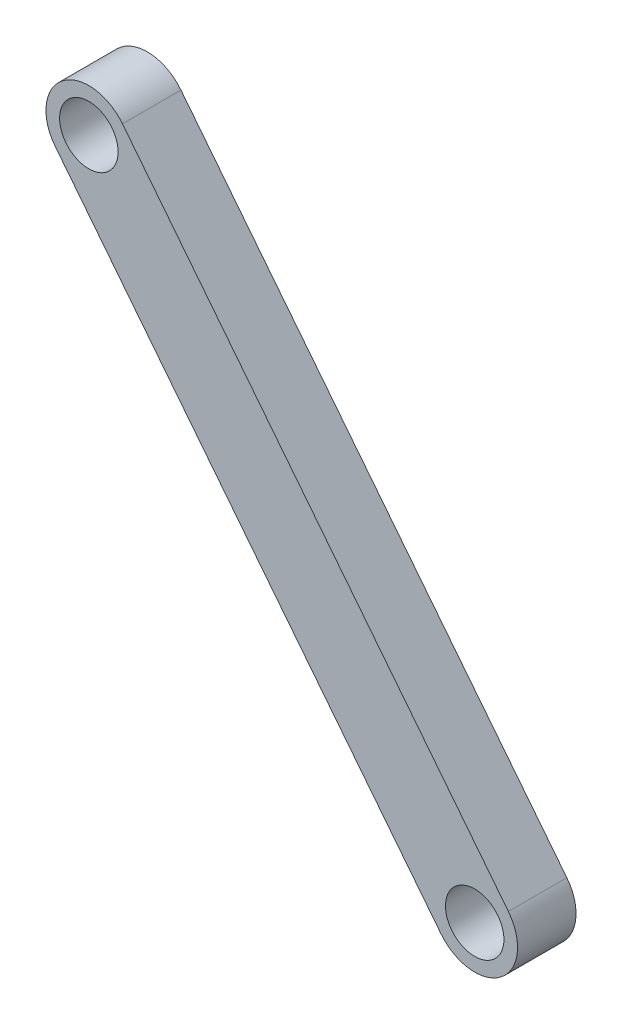
SolidWorks part; units mm, degrees
ref_plane "Plan de face" through (0, 0, 0) normal (0, 0, 1) x (1, 0, 0)
ref_plane "Plan de dessus" through (0, 0, 0) normal (0, 1, 0) x (1, 0, 0)
ref_plane "Plan de droite" through (0, 0, 0) normal (1, 0, 0) x (0, 0, -1)
sketch "Esquisse1" plane through (0, 0, 0) normal (0, 0, 1) x (1, 0, 0)
  line L0 (68.7632, 459.6651) -> (149.8144, 401.0927) construction
  line L1 (0, 0) -> (19.8, -25.1) construction
  line L2 (1.7273, 1.3625) -> (21.5273, -23.7375)
  line L3 (-1.7273, -1.3625) -> (18.0727, -26.4625)
  circle A0 centre (0, 0) radius 1.5
  circle A1 centre (19.8, -25.1) radius 1.5
  arc A2 (1.7273, 1.3625) -> (-1.7273, -1.3625) centre (0, 0) ccw
  arc A3 (18.0727, -26.4625) -> (21.5273, -23.7375) centre (19.8, -25.1) ccw
  point P7 (9.9, -12.55)
extrude "Boss.-Extru.1" add sketch "Esquisse1" along normal blind 3
